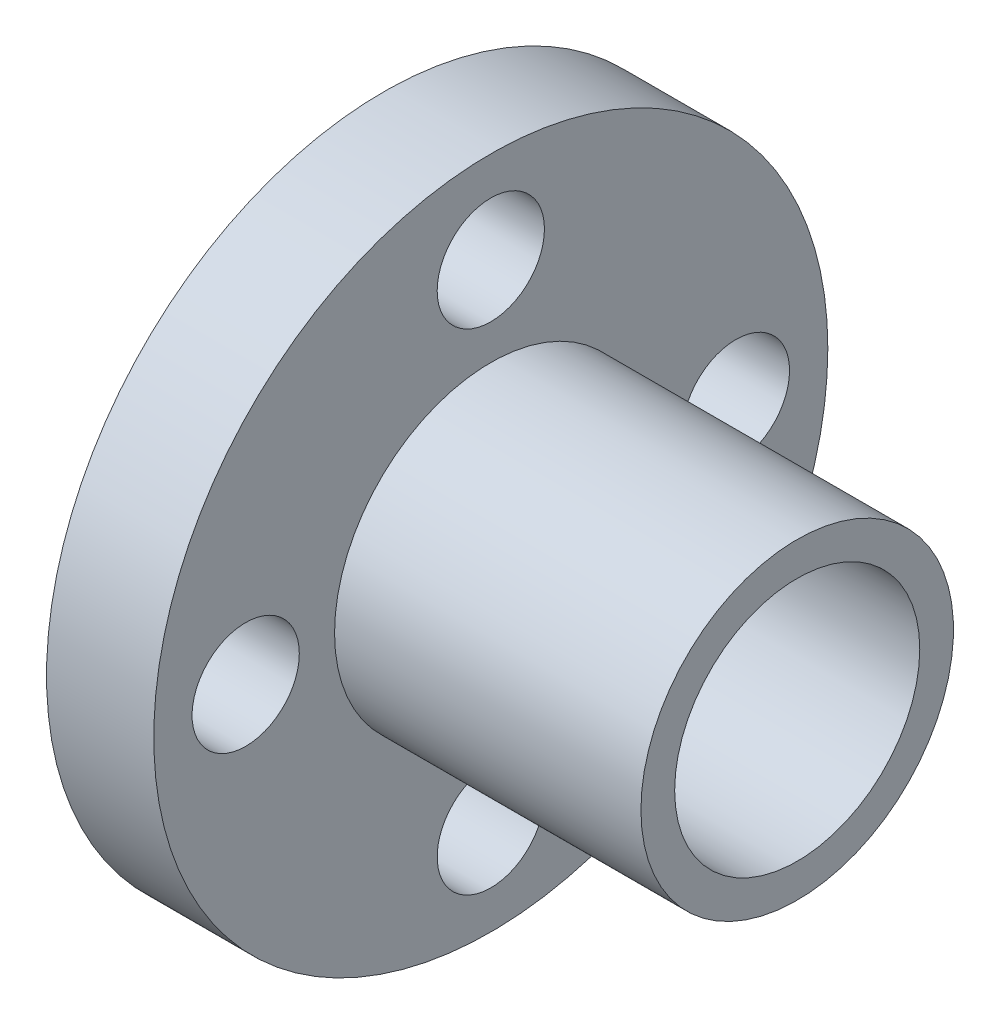
SolidWorks part; units mm, degrees
ref_plane "前视基准面" through (0, 0, 0) normal (0, 0, 1) x (1, 0, 0)
ref_plane "上视基准面" through (0, 0, 0) normal (0, 1, 0) x (1, 0, 0)
ref_plane "右视基准面" through (0, 0, 0) normal (1, 0, 0) x (0, 0, -1)
sketch "草图1" plane through (0, 0, 0) normal (1, 0, 0) x (0, 0, -1)
  circle A0 centre (0, 0) radius 11
  dimension "D1" = 22
extrude "凸台-拉伸1" add sketch "草图1" along normal blind 3.5 contours A0
sketch "草图2" plane through (0, 0, 0) normal (-1, 0, 0) x (0, 0, 1)
  circle A0 centre (0, 0) radius 5.1
  dimension "D1" = 10.2
extrude "凸台-拉伸2" add sketch "草图2" along normal blind 1.5 and the other way blind 13.5
sketch "草图3" plane through (-1.5, 0, 0) normal (-1, 0, 0) x (0, 0, 1)
  circle A0 centre (0, 0) radius 4
  dimension "D1" = 8
extrude "切除-拉伸1" cut sketch "草图3" against normal through all
sketch "草图4" plane through (0, 0, 0) normal (-1, 0, 0) x (0, 0, 1)
  line L0 (0, 0) -> (0, 8) construction
  circle A0 centre (0, 8) radius 1.75
  dimension "D1" = 3.5
  dimension "D2" = 8
extrude "切除-拉伸2" cut sketch "草图4" against normal through all
pattern_circular "阵列(圆周)1" count 4 over 360 about axis through (0, 0, 0) along (1, 0, 0) of "切除-拉伸2"
